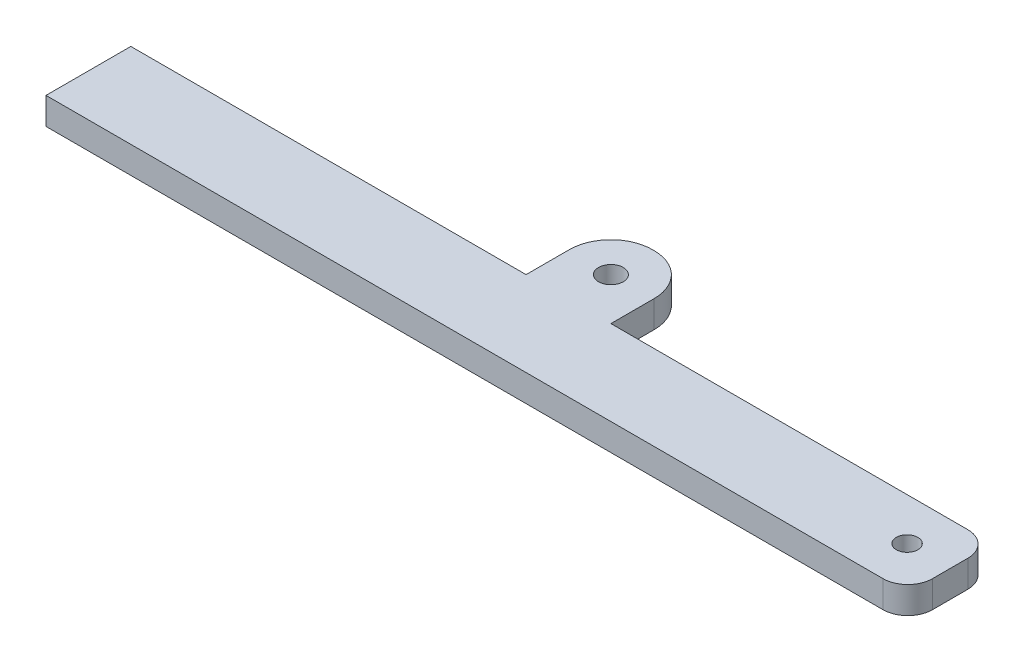
SolidWorks part; units mm, degrees
ref_plane "Front Plane" through (0, 0, 0) normal (0, 0, 1) x (1, 0, 0)
ref_plane "Top Plane" through (0, 0, 0) normal (0, 1, 0) x (1, 0, 0)
ref_plane "Right Plane" through (0, 0, 0) normal (1, 0, 0) x (0, 0, -1)
sketch "Sketch1" plane through (0, 0, 0) normal (0, 1, 0) x (1, 0, 0)
  line L0 (56.6, 10) -> (101.6, 10)
  line L1 (0, 0) -> (101.6, 0)
  line L2 (0, 0) -> (0, 10)
  line L3 (0, 10) -> (46.6, 10)
  line L4 (101.6, 0) -> (101.6, 10)
  line L6 (46.6, 10) -> (46.6, 15.1)
  line L7 (51.5, 20) -> (51.7, 20)
  line L8 (56.6, 10) -> (56.6, 15.1)
  circle A0 centre (51.6, 15) radius 1.4605
  arc A1 (56.6, 15.1) -> (51.7, 20) centre (51.7, 15.1) ccw
  arc A2 (46.6, 15.1) -> (51.5, 20) centre (51.5, 15.1) cw
  circle A3 centre (96.52, 5) radius 1.27
  point P13 (56.6, 20)
  point P16 (46.6, 20)
  point P19 (0, 0)
  point P20 (0, 5)
  dimension "D4" = 2.921
  dimension "D7" = 4.9
  dimension "D8" = 2.54
  dimension "D10" = 5.08
  dimension "D1" = 10
  dimension "D2" = 101.6
  dimension "D3" = 10
  dimension "D5" = 5
  dimension "D6" = 5
  dimension "10" = 10
  dimension "D9" = 45
extrude "Boss-Extrude1" add sketch "Sketch1" along normal blind 3.175
fillet "Fillet1" radius 2.921 2 edges at (101.6, 1.5875, 0) (101.6, 1.5875, -10)
sketch "Sketch2" [suppressed] plane through (0, 0, 0) normal (0, -1, 0) x (1, 0, 0)
  line L0 (61.6, -10) -> (0, -10) construction
  line L1 (61.6, -10) -> (71.6, -10)
  line L2 (61.6, -10) -> (61.6, -20)
  line L3 (61.6, -20) -> (71.6, -20)
  line L4 (71.6, -10) -> (71.6, -20)
  line L5 (61.6, -15.1) -> (61.6, -10) construction
  line L6 (66.7, -20) -> (66.5, -20) construction
  dimension "D1" = 10
extrude "Cut-Extrude1" [suppressed] cut sketch "Sketch2" against normal through all
sketch "Sketch3" [suppressed] plane through (0, 0, 0) normal (0, -1, 0) x (1, 0, 0)
  line L0 (0, 0) -> (98.679, 0) construction
  line L1 (61.6, 0) -> (101.6, 0)
  line L3 (61.6, -10) -> (101.6, -10)
  line L4 (101.6, 0) -> (101.6, -10)
  line L5 (101.6, -2.921) -> (101.6, -7.079) construction
  line L6 (98.679, -10) -> (0, -10) construction
  line L7 (61.6, 0) -> (61.6, -10)
  line L8 (0, -10) -> (0, 0)
  line L11 (0, -10) -> (35, 0)
  line L12 (35, 0) -> (0, 0)
  dimension "D1" = 40
  dimension "D2" = 35
extrude "Cut-Extrude2" [suppressed] cut sketch "Sketch3" against normal through all
